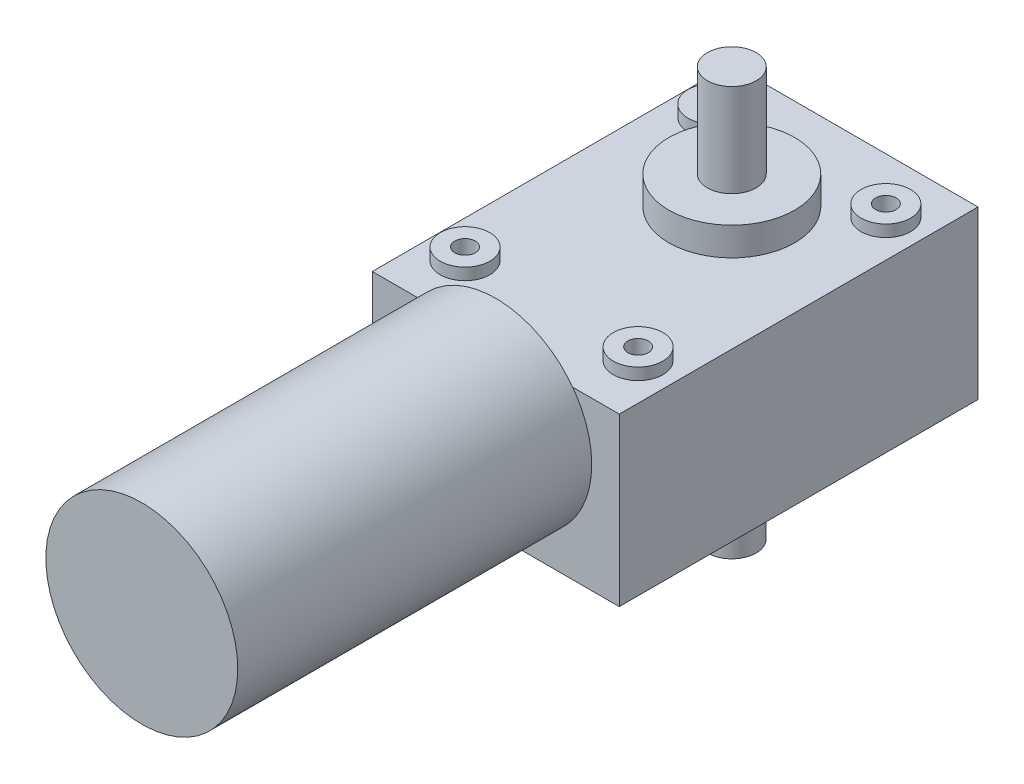
SolidWorks part; units mm, degrees
ref_plane "Front Plane" through (0, 0, 0) normal (0, 0, 1) x (1, 0, 0)
ref_plane "Top Plane" through (0, 0, 0) normal (0, 1, 0) x (1, 0, 0)
ref_plane "Right Plane" through (0, 0, 0) normal (1, 0, 0) x (0, 0, -1)
sketch "Sketch1" plane through (0, 0, 0) normal (0, 1, 0) x (1, 0, 0)
  line L1 (0, 0) -> (39.878, 0)
  line L2 (0, 0) -> (0, 57.912)
  line L3 (0, 57.912) -> (39.878, 57.912)
  line L4 (39.878, 0) -> (39.878, 57.912)
  dimension "D1" = 57.912
  dimension "D2" = 39.878
extrude "Boss-Extrude1" add sketch "Sketch1" along normal blind 26.924
sketch "Sketch22" plane through (0, 0, 0) normal (0, -1, 0) x (1, 0, 0)
  circle A0 centre (0.508, -0.508) radius 0.508
extrude "Boss-Extrude9" add sketch "Sketch22" along normal blind 0.508 separate body
sketch "Sketch3" plane through (0, 26.924, 0) normal (0, 1, 0) x (1, 0, 0)
  circle A0 centre (19.939, 38.1) radius 10.16
  dimension "D1" = 20.32
extrude "Boss-Extrude2" add sketch "Sketch3" along normal blind 4.572
sketch "Sketch4" plane through (0, 0, 0) normal (0, -1, 0) x (1, 0, 0)
  circle A0 centre (19.939, -38.1) radius 10.16
  dimension "D1" = 20.32
extrude "Boss-Extrude3" add sketch "Sketch4" along normal blind 4.572
sketch "Sketch5" plane through (0, 31.496, 0) normal (0, 1, 0) x (1, 0, 0)
  circle A0 centre (19.939, 38.1) radius 3.937
  dimension "D1" = 7.874
extrude "Boss-Extrude4" add sketch "Sketch5" along normal blind 14.986
sketch "Sketch7" plane through (0, -4.572, 0) normal (0, -1, 0) x (1, 0, 0)
  circle A0 centre (19.939, -38.1) radius 3.937
extrude "Boss-Extrude5" add sketch "Sketch7" along normal blind 14.986
sketch "Sketch8" plane through (0, 0, 0) normal (0, 0, 1) x (1, 0, 0)
  circle A0 centre (19.939, 17.653) radius 15.494
  dimension "D1" = 30.988
extrude "Boss-Extrude6" add sketch "Sketch8" along normal blind 57.15 separate body
sketch "Sketch10" plane through (0, 26.924, 0) normal (0, 1, 0) x (1, 0, 0)
  circle A0 centre (5.9563, 9.017) radius 4.0005
extrude "Boss-Extrude7" add sketch "Sketch10" along normal blind 1.905
hole_wizard "M4x0.7 Tapped Hole1" positions "Sketch15" profile "Sketch16" tap size "M4x0.7" standard "ANSI Metric"
sketch "Sketch15" plane through (0, 28.829, 0) normal (0, 1, 0) x (1, 0, 0)
  point P0 (5.9563, 9.017)
cosmetic thread "Hole Thread2" parameters "D1"=7.874, "D2"=4
sketch "Sketch16" plane through (5.9563, 28.829, -9.017) normal (1, 0, 0) x (0, 0, 1)
  line L0 (0, 0) -> (0, 10.0084)
  line L1 (0, 10.0084) -> (1.65, 9.017)
  line L2 (1.65, 9.017) -> (1.65, 0)
  line L5 (1.65, 0) -> (0, 0)
  line L10 (0, 10.0084) -> (-1.65, 9.017) construction
  line L11 (0, -6.35) -> (0, 107.95) construction
  dimension "Tap Drill Dia." = 3.3
  dimension "Tap Drill Depth" = 9.017
  dimension "Drill Angle" = 118
pattern_linear "LPattern1" count 2 spacing 40 along (0, 0, -1) count 2 spacing 27.94 along (1, 0, 0) of "Boss-Extrude7", "M4x0.7 Tapped Hole1"
sketch "Sketch18" plane through (0, 0, 0) normal (0, -1, 0) x (1, 0, 0)
  circle A0 centre (5.9563, -9.017) radius 4.0005
extrude "Boss-Extrude8" add sketch "Sketch18" along normal blind 1.905
hole_wizard "M4x0.7 Tapped Hole2" positions "Sketch19" profile "Sketch20" tap size "M4x0.7" standard "ANSI Metric"
sketch "Sketch19" plane through (0, -1.905, 0) normal (0, -1, 0) x (-1, 0, 0)
  point P0 (-5.8154, 9.2798)
sketch "Sketch20" plane through (5.8154, -1.905, -9.2798) normal (1, 0, 0) x (0, 0, -1)
  line L0 (0, 0) -> (0, 10.1354)
  line L1 (0, 10.1354) -> (1.65, 9.144)
  line L2 (1.65, 9.144) -> (1.65, 0)
  line L5 (1.65, 0) -> (0, 0)
  line L10 (0, 10.1354) -> (-1.65, 9.144) construction
  line L11 (0, -6.35) -> (0, 107.95) construction
  dimension "Tap Drill Dia." = 3.3
  dimension "Tap Drill Depth" = 9.144
  dimension "Drill Angle" = 118
cosmetic thread "Hole Thread3" parameters "D1"=7.874, "D2"=4
pattern_linear "LPattern3" count 2 spacing 27.94 along (1, 0, 0) count 2 spacing 40 along (0, 0, -1) of "Boss-Extrude8", "M4x0.7 Tapped Hole2"
